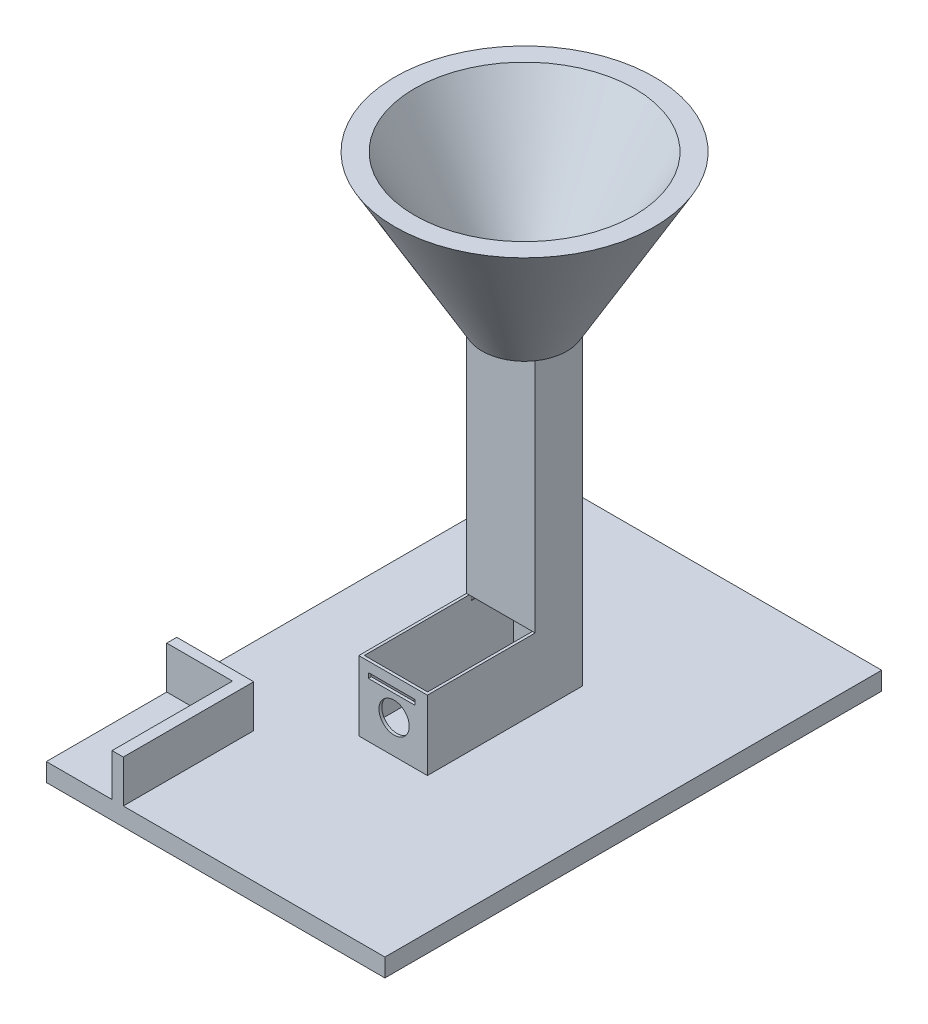
SolidWorks part; units mm, degrees
ref_plane "Front Plane" through (0, 0, 0) normal (0, 0, 1) x (1, 0, 0)
ref_plane "Top Plane" through (0, 0, 0) normal (0, 1, 0) x (1, 0, 0)
ref_plane "Right Plane" through (0, 0, 0) normal (1, 0, 0) x (0, 0, -1)
sketch "Sketch2" plane through (0, 0, 0) normal (0, 1, 0) x (1, 0, 0)
  line L1 (0, 0) -> (22.6576, 0)
  line L2 (0, 0) -> (0, 51.2643)
  line L3 (0, 51.2643) -> (22.6576, 51.2643)
  line L4 (22.6576, 0) -> (22.6576, 51.2643)
extrude "Boss-Extrude1" add sketch "Sketch2" along normal blind 2
sketch "Sketch3" plane through (0, 2, 0) normal (0, 1, 0) x (1, 0, 0)
  line L0 (0, 51.2643) -> (0, 0)
  line L1 (0.8762, 0.9533) -> (21.7814, 0.9533)
  line L2 (0.8762, 0.9533) -> (0.8762, 50.2442)
  line L3 (0.8762, 50.2442) -> (21.7814, 50.2442)
  line L4 (21.7814, 0.9533) -> (21.7814, 50.2442)
  line L5 (0, 0) -> (22.6576, 0)
  line L6 (22.6576, 0) -> (22.6576, 51.2643)
  line L7 (22.6576, 51.2643) -> (0, 51.2643)
extrude "Boss-Extrude2" add sketch "Sketch3" along normal blind 21
sketch "Sketch5" plane through (0, 23, 0) normal (0, 1, 0) x (1, 0, 0)
  line L1 (0, 51.2643) -> (0, 0) construction
  line L2 (22.6576, 0) -> (22.6576, 51.2643) construction
  line L3 (22.6576, 37.4503) -> (22.6576, 51.2643)
  line L4 (22.6576, 51.2643) -> (0, 51.2643)
  line L5 (0, 51.2643) -> (0, 35.5807)
  line L6 (0, 35.5807) -> (22.6576, 35.5807)
  line L7 (22.6576, 35.5807) -> (22.6576, 37.4503)
extrude "Boss-Extrude3" add sketch "Sketch5" along normal blind 78
sketch "Sketch6" plane through (0, 101, 0) normal (0, 1, 0) x (1, 0, 0)
  line L1 (0.6734, 50.6255) -> (21.9587, 50.6255)
  line L2 (0.6734, 50.6255) -> (0.6734, 36.3465)
  line L3 (0.6734, 36.3465) -> (21.9587, 36.3465)
  line L4 (21.9587, 50.6255) -> (21.9587, 36.3465)
extrude "Cut-Extrude1" cut sketch "Sketch6" against normal blind 80
sketch "Sketch11" plane through (0, 101, 0) normal (0, 1, 0) x (1, 0, 0)
  circle A1 centre (11.3288, 43.4225) radius 14
  point P0 (0, 0)
extrude "Boss-Extrude4" add sketch "Sketch11" along normal blind 50 draft 30 draft outward yes
sketch "Sketch12" plane through (0, 151, 0) normal (0, 1, 0) x (1, 0, 0)
  circle A0 centre (11.3288, 43.4225) radius 36.31
extrude "Cut-Extrude2" cut sketch "Sketch12" against normal blind 51 draft 30
sketch "Sketch14" plane through (0, 0, 0) normal (0, 0, 1) x (1, 0, 0)
  line L0 (22.6576, 23) -> (22.6576, 0) construction
  circle A0 centre (11.6576, 11.0764) radius 5
  point P4 (0, 0)
  dimension "D1" = 11
extrude "Cut-Extrude4" cut sketch "Sketch14" against normal blind 22
sketch "Sketch15" plane through (0, 0, 0) normal (0, 0, 1) x (1, 0, 0)
  line L0 (3.1516, 19.7143) -> (18.5616, 19.7143)
  line L1 (18.5616, 19.7143) -> (18.5616, 18.0454)
  line L2 (18.5616, 18.0454) -> (3.1516, 18.0454)
  line L3 (3.1516, 18.0454) -> (3.1516, 19.7143)
extrude "Cut-Extrude5" cut sketch "Sketch15" against normal blind 22
sketch "Sketch16" plane through (0, 0, 0) normal (0, -1, 0) x (1, 0, 0)
  line L1 (-44.2789, -105.1512) -> (67.5398, -105.1512)
  line L2 (-44.2789, -105.1512) -> (-44.2789, 58.9163)
  line L3 (-44.2789, 58.9163) -> (67.5398, 58.9163)
  line L4 (67.5398, -105.1512) -> (67.5398, 58.9163)
extrude "Boss-Extrude10" add sketch "Sketch16" along normal blind 6
sketch "Sketch17" plane through (0, 0, 0) normal (0, 1, 0) x (1, 0, 0)
  line L0 (-44.2789, -19.1589) -> (-22.5583, -19.1589)
  line L1 (-44.2789, -58.9163) -> (-44.2789, 105.1512) construction
  line L2 (-22.5583, -19.1589) -> (-22.5583, -58.9163)
  line L3 (-22.5583, -58.9163) -> (-18.8596, -58.9163)
  line L4 (67.5398, -58.9163) -> (-44.2789, -58.9163) construction
  line L5 (-18.8596, -58.9163) -> (-18.8596, -15.832)
  line L6 (-18.8596, -15.832) -> (-44.2789, -15.832)
  line L7 (-44.2789, -15.832) -> (-44.2789, -19.1589)
extrude "Boss-Extrude11" add sketch "Sketch17" along normal blind 14
sketch "Sketch18" plane through (0, 2, 0) normal (0, 1, 0) x (1, 0, 0)
  line L0 (4.2385, 49.5208) -> (19.4511, 49.0529)
  line L1 (19.4511, 49.0529) -> (19.4511, 47.5108)
  line L2 (19.4511, 47.5108) -> (4.2385, 47.9787)
  line L3 (4.2385, 47.9787) -> (4.2385, 49.5208)
  point P2 (1.2015, 44.7415)
extrude "Cut-Extrude6" cut sketch "Sketch18" against normal blind 14
